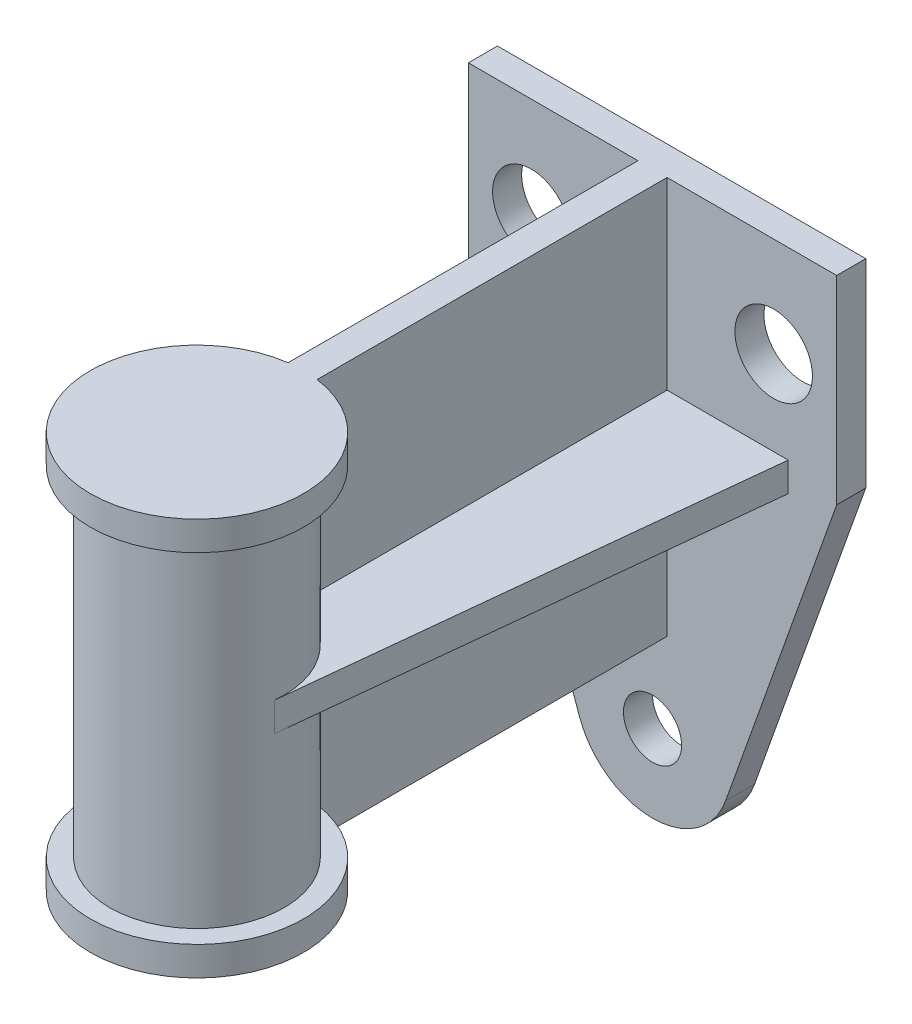
SolidWorks part; units mm, degrees
ref_plane "Front Plane" through (0, 0, 0) normal (0, 0, 1) x (1, 0, 0)
ref_plane "Top Plane" through (0, 0, 0) normal (0, 1, 0) x (1, 0, 0)
ref_plane "Right Plane" through (0, 0, 0) normal (1, 0, 0) x (0, 0, -1)
sketch "Sketch1" plane through (0, 0, 0) normal (0, 1, 0) x (1, 0, 0)
  circle A0 centre (0, 0) radius 18
  dimension "D1" = 36
extrude "Boss-Extrude1" add sketch "Sketch1" along normal mid plane 82 contours A0
ref_plane "Plane1" through (0, 0, -100) normal (0, 0, 1) x (1, 0, 0)
sketch "Sketch3" plane through (0, 0, -100) normal (0, 0, 1) x (1, 0, 0)
  line L0 (-38, 41) -> (38, 41)
  line L1 (38, 41) -> (38, 0)
  line L2 (38, 0) -> (15.0724, -64.3687)
  line L3 (0, 0) -> (0, -100.0191) construction
  line L4 (-38, 41) -> (-38, 0)
  line L5 (-38, 0) -> (-15.0724, -64.3687)
  arc A0 (-15.0724, -64.3687) -> (15.0724, -64.3687) centre (0, -59) ccw
  circle A1 centre (0, -59) radius 6
  dimension "D1" = 32
  dimension "D5" = 12
  dimension "D2" = 100
  dimension "D3" = 41
  dimension "D4" = 76
extrude "Boss-Extrude2" add sketch "Sketch3" along normal blind 6 separate body
sketch "Sketch4" plane through (0, 0, 0) normal (1, 0, 0) x (0, 0, -1)
  line L0 (13, 41) -> (94, 41)
  line L1 (94, 41) -> (94, -41)
  line L2 (94, -64.3687) -> (94, 0) construction
  line L3 (94, -41) -> (13, -41)
  line L4 (13, 41) -> (13, -41)
  line L5 (-18, -41) -> (18, -41) construction
  dimension "D1" = 13
extrude "Boss-Extrude3" add sketch "Sketch4" along normal mid plane 6
sketch "Sketch6" plane through (0, 41, 0) normal (0, 1, 0) x (1, 0, 0)
  circle A0 centre (0, 0) radius 22
  dimension "D1" = 44
extrude "Boss-Extrude4" add sketch "Sketch6" against normal blind 6
sketch "Sketch7" plane through (0, -41, 0) normal (0, -1, 0) x (1, 0, 0)
  circle A0 centre (0, 0) radius 22
  dimension "D1" = 44
extrude "Boss-Extrude5" add sketch "Sketch7" against normal blind 6
sketch "Sketch8" plane through (0, 0, 0) normal (0, 1, 0) x (1, 0, 0)
  line L0 (-28, 94) -> (-17.901, -1.8854)
  line L1 (-3, 94) -> (-38, 94) construction
  line L2 (-28, 94) -> (28, 94)
  line L3 (38, 94) -> (3, 94) construction
  line L4 (28, 94) -> (17.901, -1.8854)
  line L5 (0, 0) -> (0, 120.4474) construction
  arc A0 (17.901, -1.8854) -> (-17.901, -1.8854) centre (0, 0) ccw
  dimension "D1" = 36
  dimension "D2" = 56
extrude "Boss-Extrude6" add sketch "Sketch8" along normal mid plane 6 contours L0 A0 L4 L2
hole_wizard "Hole1" positions "Sketch9" profile "Sketch10" legacy
sketch "Sketch9" plane through (0, 0, -94) normal (0, 0, 1) x (1, 0, 0)
  line L0 (0, 0) -> (0, 73.9311) construction
  line L2 (38, 41) -> (3, 41) construction
  point P0 (25, 20.5)
  point P2 (-25, 20.5)
  point P9 (0, 0)
  point P10 (0, 0)
  dimension "D1" = 50
  dimension "D2" = 20.5
sketch "Sketch10" plane through (25, 20.5, -94) normal (1, 0, 0) x (0, -1, 0)
  line L0 (0, 0) -> (0, 6)
  line L1 (0, 6) -> (8, 6)
  line L2 (8, 6) -> (8, 0)
  line L3 (8, 0) -> (0, 0)
  line L4 (0, 110) -> (0, -10) construction
  dimension "Diameter" = 16
  dimension "Depth" = 6
